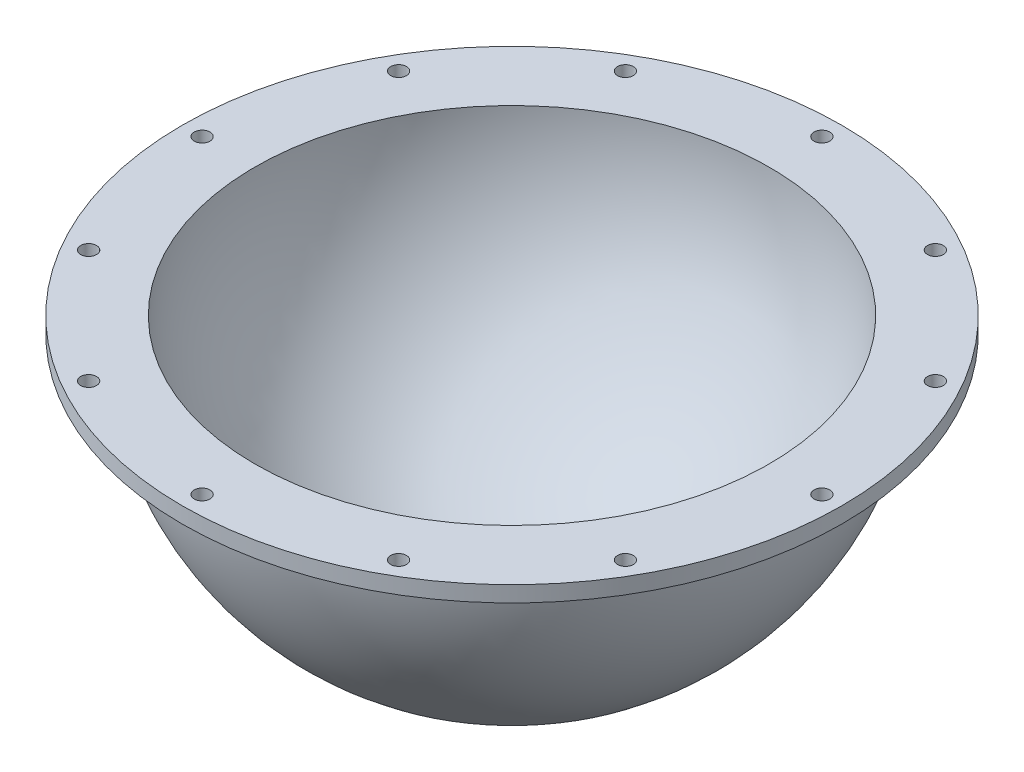
SolidWorks part; units mm, degrees
ref_plane "Front Plane" through (0, 0, 0) normal (0, 0, 1) x (1, 0, 0)
ref_plane "Top Plane" through (0, 0, 0) normal (0, 1, 0) x (1, 0, 0)
ref_plane "Right Plane" through (0, 0, 0) normal (1, 0, 0) x (0, 0, -1)
sketch "Sketch1" plane through (0, 0, 0) normal (0, 1, 0) x (1, 0, 0)
  line L0 (0, 220) -> (0, 195)
  line L1 (0, -195) -> (0, -220)
  line L2 (0, 220) -> (0, -220) construction
  arc A0 (0, 220) -> (0, -220) centre (0, 0) ccw
  arc A1 (0, 195) -> (0, -195) centre (0, 0) ccw
  dimension "D1" = 220
  dimension "D2" = 25
revolve "Revolve1" add sketch "Sketch1" angle 180 about L2
ref_axis "Axis1" through (0, 0, 0) along (0, 1, 0)
sketch "Sketch3" plane through (0, 0, 0) normal (1, 0, 0) x (0, 0, -1)
  line L0 (-220, 0) -> (-250, 0)
  line L1 (-250, 0) -> (-250, -12)
  line L2 (-250, -12) -> (-219.6725, -12)
  line L3 (-250, 0) -> (250, 0) construction
  arc A0 (-220, 0) -> (220, 0) centre (0, 0) ccw construction
  arc A1 (-220, 0) -> (-219.6725, -12) centre (0, 0) ccw
  point P10 (-235, 0)
  dimension "D1" = 500
  dimension "D2" = 12
revolve "Revolve2" add sketch "Sketch3" angle 360 about axis through (0, 0, 0) along (0, 1, 0)
sketch "Sketch10" plane through (0, 0, 0) normal (0, 1, 0) x (1, 0, 0)
  circle A0 centre (0, 0) radius 235 construction
  circle A1 centre (0, 235) radius 6
  circle A2 centre (-117.5, 203.516) radius 6
  circle A3 centre (-203.516, 117.5) radius 6
  circle A4 centre (-235, 0) radius 6
  circle A5 centre (-203.516, -117.5) radius 6
  circle A6 centre (-117.5, -203.516) radius 6
  circle A7 centre (0, -235) radius 6
  circle A8 centre (117.5, -203.516) radius 6
  circle A9 centre (203.516, -117.5) radius 6
  circle A10 centre (235, 0) radius 6
  circle A11 centre (203.516, 117.5) radius 6
  circle A12 centre (117.5, 203.516) radius 6
  point P30 (0, 0)
  dimension "D1" = 470
  dimension "D2" = 12
  dimension "D3" = 12
extrude "Cut-Extrude1" cut sketch "Sketch10" against normal through all
equation "\"mbtOD\" = 850"
equation "\"mbtT\" = 6"
equation "\"mbtL\" = 1500"
equation "\"mbtFlangeOD\" = 950"
equation "\"mbtFlangeT\" = 12"
equation "\"mbtFlangeBoltCircleDia\" = 650"
equation "\"mbtFlangeHoleDia\" = 12"
equation "\"mbtOringSize\" = 10 "
equation "\"mbtOringDia\" = 620"
equation "\"mbtWidth\" = 2250"
equation "\"skiWidth\" = 1250"
equation "\"mbtCapL\" = 500"
equation "\"vbtRearOD\" = 500"
equation "\"vbtRearT\" = 6.25"
equation "\"vbtRearFlangeOD\" = 600"
equation "\"vbtRearFlangeT\" = 12"
equation "\"vbtRearBoltHoleDia\" = 12"
equation "\"vbtFrontOD\" = 440"
equation "\"vbtFrontT\" = 25"
equation "\"vbtFrontFlangeOD\" = 500"
equation "\"vbtFrontFlangeT\" = 12"
equation "\"vbtFrontBoltHoleDia\" = 12"
equation "\"D1@Sketch1\"=\"vbtFrontOD\"/2"
equation "\"D2@Sketch1\"=\"vbtFrontT\""
equation "\"D1@Sketch3\"=\"vbtFrontFlangeOD\""
equation "\"D2@Sketch3\"=\"vbtFrontFlangeT\""
equation "\"D1@Sketch10\"=(\"vbtFrontOD\"+\"vbtFrontFlangeOD\")/2"
equation "\"D2@Sketch10\"=\"vbtFrontBoltHoleDia\""
